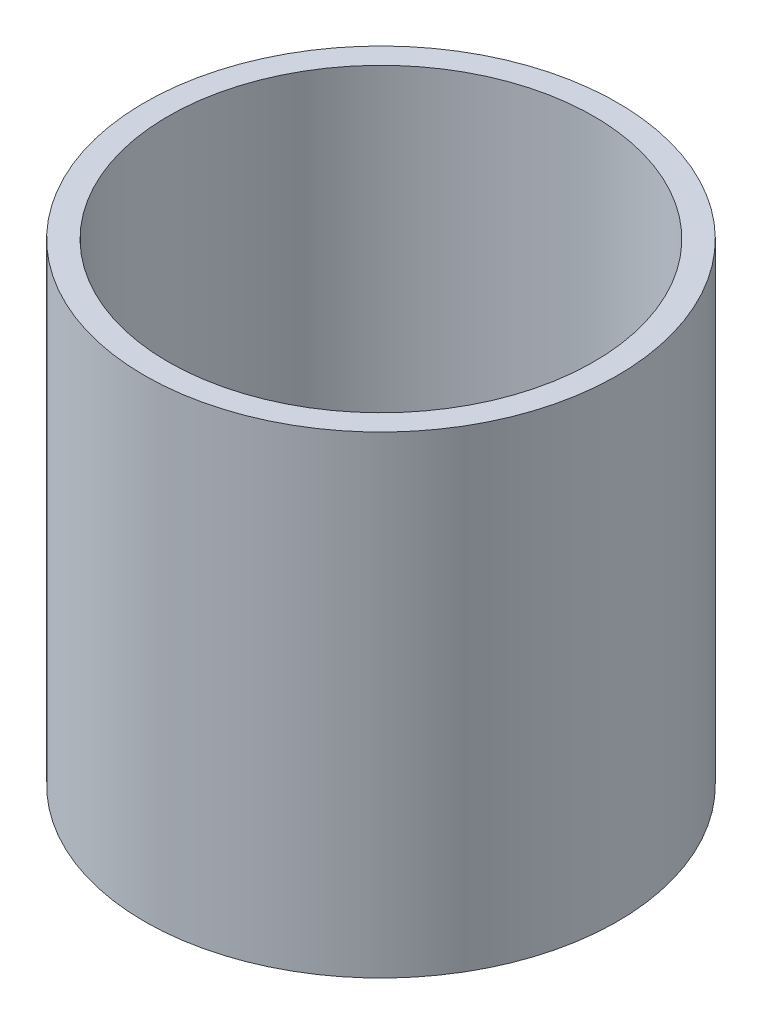
SolidWorks part; units mm, degrees
material "ABS"
ref_plane "Plano frontal" through (0, 0, 0) normal (0, 0, 1) x (1, 0, 0)
ref_plane "Plano superior" through (0, 0, 0) normal (0, 1, 0) x (1, 0, 0)
ref_plane "Plano direito" through (0, 0, 0) normal (1, 0, 0) x (0, 0, -1)
sketch "Esboço1" plane through (0, 0, 0) normal (0, 1, 0) x (1, 0, 0)
  circle A0 centre (0, 0) radius 25
  dimension "D2" = 50
extrude "Ressalto-extrusão1" add sketch "Esboço1" along normal blind 50
sketch "Esboço2" plane through (0, 50, 0) normal (0, 1, 0) x (1, 0, 0)
  circle A0 centre (0, 0) radius 22.5
  circle A1 centre (0, 0) radius 25 construction
  dimension "D1" = 2.5
extrude "Corte-extrusão1" cut sketch "Esboço2" against normal blind 47.5
